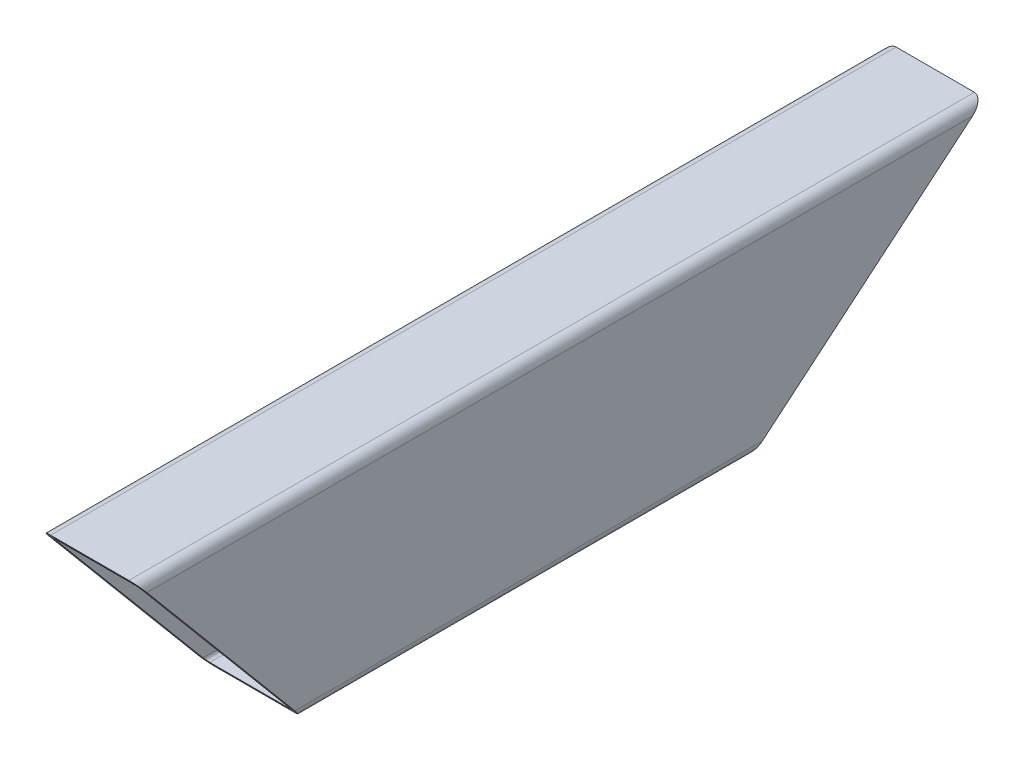
SolidWorks part; units mm, degrees
material "6061-T6 (SS)"
ref_plane "Front" through (0, 0, 0) normal (0, 0, 1) x (1, 0, 0)
ref_plane "Top" through (0, 0, 0) normal (0, 1, 0) x (1, 0, 0)
ref_plane "Right" through (0, 0, 0) normal (1, 0, 0) x (0, 0, -1)
sketch "Sketch3" plane through (0, 0, 0) normal (1, 0, 0) x (0, 0, -1)
  line L0 (-60.5411, -25.4) -> (-176.5918, -25.4)
  line L1 (-176.5918, -25.4) -> (-219.2181, 25.4)
  line L2 (-219.2181, 25.4) -> (0, 25.4)
  line L3 (0, 25.4) -> (-60.5411, -25.4)
  point P3 (-10.1607, 42.3214)
  point P6 (0, 39.5922)
  point P8 (-30.2705, 0)
  point P9 (-232.4789, 25.4)
  point P10 (-201.4548, 25.4)
  dimension "D1" = 50.8
  dimension "D2" = 88.9
  dimension "D3" = 40
sketch "Sketch1" plane through (0, 0, 0) normal (0, 0, 1) x (1, 0, 0)
  line L1 (-10.16, -25.4) -> (10.16, -25.4)
  line L2 (-12.7, -22.86) -> (-12.7, 22.86)
  line L3 (-10.16, 25.4) -> (10.16, 25.4)
  line L4 (12.7, -22.86) -> (12.7, 22.86)
  line L5 (-12.7, -25.4) -> (12.7, 25.4) construction
  line L6 (-12.7, 25.4) -> (12.7, -25.4) construction
  arc A0 (-10.16, -25.4) -> (-12.7, -22.86) centre (-10.16, -22.86) cw
  arc A1 (10.16, -25.4) -> (12.7, -22.86) centre (10.16, -22.86) ccw
  arc A2 (10.16, 25.4) -> (12.7, 22.86) centre (10.16, 22.86) cw
  arc A3 (-12.7, 22.86) -> (-10.16, 25.4) centre (-10.16, 22.86) cw
  point P0 (0, 0)
  dimension "D3" = 2.54
  dimension "D1" = 25.4
  dimension "D2" = 50.8
extrude "Extrude-Thin1" add sketch "Sketch1" along normal up to vertex (219.2181 mm away) thin up to point (0, 25.4, 219.2181) thin type one direction reverse wall 1.5875
sketch "Sketch2" plane through (12.7, 0, 0) normal (1, 0, 0) x (0, 0, -1)
  line L0 (-219.2181, 25.4) -> (-176.5918, -25.4)
  line L1 (-219.2181, -25.4) -> (0, -25.4) construction
  line L2 (-176.5918, -25.4) -> (-219.2181, -25.4)
  line L3 (-219.2181, -25.4) -> (-219.2181, 25.4)
  line L4 (0, 25.4) -> (-60.5411, -25.4)
  line L5 (-60.5411, -25.4) -> (0, -25.4)
  line L6 (0, -25.4) -> (0, 25.4)
  line L7 (0, 25.4) -> (-60.5411, -25.4) construction
  line L8 (-176.5918, -25.4) -> (-219.2181, 25.4) construction
extrude "Cut-Extrude1" cut sketch "Sketch2" against normal through all
